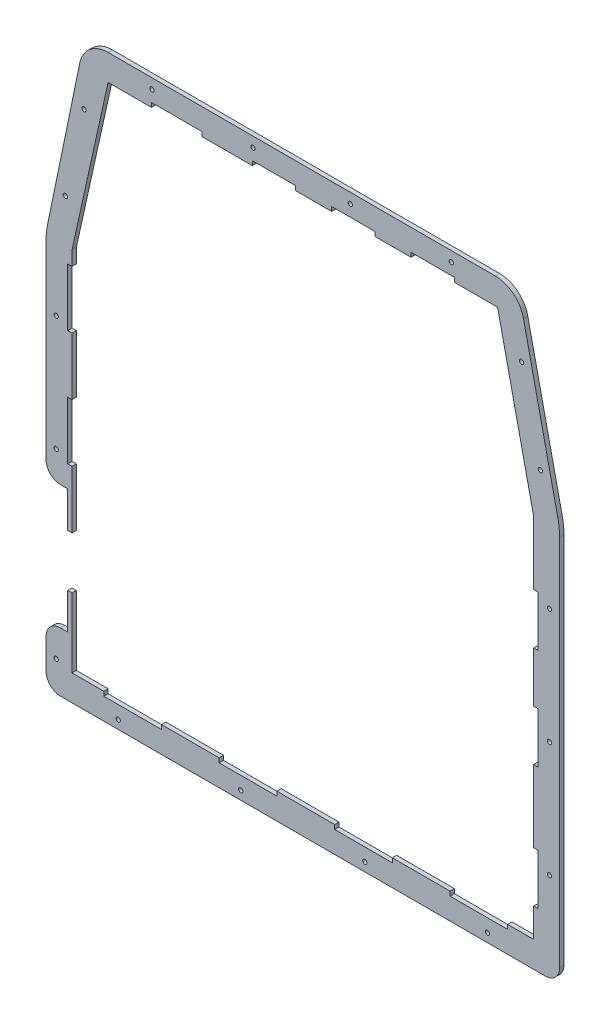
SolidWorks part; units mm, degrees
ref_plane "Front Plane" through (0, 0, 0) normal (0, 0, 1) x (1, 0, 0)
ref_plane "Top Plane" through (0, 0, 0) normal (0, 1, 0) x (1, 0, 0)
ref_plane "Right Plane" through (0, 0, 0) normal (1, 0, 0) x (0, 0, -1)
ref_plane "Plane1" through (0, 0, -1194.953) normal (0, 0, 1) x (1, 0, 0)
sketch "Sketch1" plane through (0, 0, -1194.953) normal (0, 0, 1) x (1, 0, 0)
  line L1 (-160, 1173.2804) -> (160, 1173.2804)
  line L2 (160, 1173.2804) -> (160, 1427.2804)
  line L3 (-135, 1540.2804) -> (135, 1540.2804)
  line L4 (-139, 1540.2804) -> (-105, 1540.2804) construction
  line L5 (160, 1427.2804) -> (135, 1540.2804)
  line L6 (-160, 1173.2804) -> (-160, 1282.2804)
  line L8 (-154.5872, 1542.3231) -> (-176.9679, 1433.8872)
  line L9 (152.9219, 1542.6007) -> (176.8195, 1434.5836)
  line L10 (-168, 1155.2804) -> (168, 1155.2804)
  line L11 (178, 1165.2804) -> (178, 1423.7829)
  line L12 (133.3941, 1558.2804) -> (-135, 1558.2804)
  line L13 (-178, 1423.7804) -> (-178, 1292.2804)
  line L15 (-168, 1196.2804) -> (-163, 1196.2804)
  line L20 (-178, 1186.2804) -> (-178, 1165.2804)
  line L21 (-168, 1282.2804) -> (-163, 1282.2804)
  line L22 (-163, 1427.2804) -> (-163, 1417.2804) construction
  line L23 (-163, 1282.2804) -> (-163, 1196.2804)
  line L25 (-160, 1427.2804) -> (-160, 1282.2804)
  line L26 (-135, 1540.2804) -> (-160, 1427.2804)
  arc A0 (152.9219, 1542.6007) -> (133.3941, 1558.2804) centre (133.3941, 1538.2804) ccw
  arc A1 (-154.5872, 1542.3231) -> (-135, 1558.2804) centre (-135, 1538.2804) cw
  arc A2 (168, 1155.2804) -> (178, 1165.2804) centre (168, 1165.2804) ccw
  arc A3 (-178, 1165.2804) -> (-168, 1155.2804) centre (-168, 1165.2804) ccw
  arc A4 (176.8195, 1434.5836) -> (178, 1423.7829) centre (128, 1423.7829) cw
  arc A5 (-176.9679, 1433.8872) -> (-178, 1423.7804) centre (-128, 1423.7804) ccw
  arc A6 (-168, 1196.2804) -> (-178, 1186.2804) centre (-168, 1186.2804) ccw
  arc A7 (-168, 1282.2804) -> (-178, 1292.2804) centre (-168, 1292.2804) cw
  circle A8 centre (-171, 1176.2804) radius 1.5
  circle A9 centre (-128, 1161.2804) radius 1.5
  circle A10 centre (-43, 1161.2804) radius 1.5
  circle A11 centre (43, 1161.2804) radius 1.5
  circle A12 centre (128, 1161.2804) radius 1.5
  circle A13 centre (171, 1217.2804) radius 1.5
  circle A14 centre (171, 1297.2804) radius 1.5
  circle A15 centre (171, 1377.2804) radius 1.5
  circle A16 centre (151.6679, 1515.8638) radius 1.5
  circle A17 centre (164.6288, 1457.2804) radius 1.5
  circle A18 centre (-104.5872, 1551.2804) radius 1.5
  circle A19 centre (-34.5872, 1551.2804) radius 1.5
  circle A20 centre (32.9219, 1551.2804) radius 1.5
  circle A21 centre (102.9219, 1551.2804) radius 1.5
  circle A22 centre (-171, 1382.2804) radius 1.5
  circle A23 centre (-171, 1302.2804) radius 1.5
  circle A24 centre (-151.6679, 1515.8638) radius 1.5
  circle A25 centre (-164.6288, 1457.2804) radius 1.5
  point P41 (-178, 1196.2804)
  dimension "D9" = 20
  dimension "D10" = 10
  dimension "D11" = 50
  dimension "D14" = 10
  dimension "D5" = 25
  dimension "D16" = 3
  dimension "D17" = 3
  dimension "D18" = 20
  dimension "D19" = 11
  dimension "D20" = 3
  dimension "D21" = 80
  dimension "D22" = 3
  dimension "D23" = 11
  dimension "D24" = 11
  dimension "D25" = 30
  dimension "D26" = 3
  dimension "D27" = 11
  dimension "D28" = 60
  dimension "D29" = 3
  dimension "D30" = 50
  dimension "D31" = 3
  dimension "D32" = 3
  dimension "D33" = 3
  dimension "D34" = 70
  dimension "D36" = 70
  dimension "D37" = 7
  dimension "D38" = 7
  dimension "D41" = 3
  dimension "D42" = 3
  dimension "D43" = 30
  dimension "D44" = 11
  dimension "D45" = 11
  dimension "D46" = 60
  dimension "D47" = 3
  dimension "D48" = 3
  dimension "D49" = 3
  dimension "D50" = 3
  dimension "D51" = 3
  dimension "D52" = 3
  dimension "D53" = 3
  dimension "D54" = 20
  dimension "D55" = 6
  dimension "D56" = 11
  dimension "D57" = 7
  dimension "D58" = 7
  dimension "D61" = 80
  dimension "D62" = 50
  dimension "D63" = 85
  dimension "D66" = 7
  dimension "D67" = 6
  dimension "D64" = 85
  dimension "D1" = 18
  dimension "D2" = 25
  dimension "D3" = 18
  dimension "D4" = 270
  dimension "D6" = 18
  dimension "D7" = 18
  dimension "D8" = 18
  dimension "D12" = 23
  dimension "D13" = 86
  dimension "D15" = 134.5
  dimension "D35" = 50
  dimension "D39" = 7
  dimension "D40" = 7
  dimension "D59" = 50
  dimension "D60" = 80
  dimension "D65" = 50
  dimension "D68" = 6
  dimension "D69" = 6
extrude "Boss-Extrude1" add sketch "Sketch1" along normal blind 3 contours A7 L21 L23 L15 A6 L20 A3 L10 A2 L11 A4 L9 A0 L12 A1 L8 A5 L13 L6 L25 L26 L3 L5 L2 L1
sketch "Sketch2" plane through (0, 0, -1191.953) normal (0, 0, 1) x (1, 0, 0)
  line L0 (-160, 1173.2804) -> (160, 1173.2804) construction
  line L1 (-138, 1173.2804) -> (-98, 1173.2804)
  line L2 (-138, 1173.2804) -> (-138, 1170.2804)
  line L3 (-138, 1170.2804) -> (-98, 1170.2804)
  line L4 (-98, 1173.2804) -> (-98, 1170.2804)
  line L5 (-163, 1170.2804) -> (-138, 1170.2804) construction
  line L6 (-58, 1173.2804) -> (-18, 1173.2804)
  line L7 (-58, 1173.2804) -> (-58, 1170.2804)
  line L8 (-58, 1170.2804) -> (-18, 1170.2804)
  line L9 (-18, 1173.2804) -> (-18, 1170.2804)
  line L10 (-178, 1186.2804) -> (-178, 1165.2804) construction
  line L11 (22, 1173.2804) -> (62, 1173.2804)
  line L12 (22, 1173.2804) -> (22, 1170.2804)
  line L13 (22, 1170.2804) -> (62, 1170.2804)
  line L14 (62, 1173.2804) -> (62, 1170.2804)
  line L15 (102, 1173.2804) -> (142, 1173.2804)
  line L16 (102, 1173.2804) -> (102, 1170.2804)
  line L17 (102, 1170.2804) -> (142, 1170.2804)
  line L18 (142, 1173.2804) -> (142, 1170.2804)
  line L19 (-163, 1282.2804) -> (-163, 1196.2804) construction
  line L20 (-163, 1257.2804) -> (-160, 1257.2804)
  line L21 (-163, 1257.2804) -> (-163, 1221.2804)
  line L22 (-163, 1221.2804) -> (-160, 1221.2804)
  line L23 (-160, 1257.2804) -> (-160, 1221.2804)
  line L24 (-160, 1173.2804) -> (-160, 1427.2804) construction
  line L25 (-168, 1196.2804) -> (-163, 1196.2804) construction
  line L26 (-168, 1282.2804) -> (-163, 1282.2804) construction
  line L28 (-160, 1297.2804) -> (-163, 1297.2804)
  line L29 (-160, 1297.2804) -> (-160, 1337.2804)
  line L30 (-160, 1337.2804) -> (-163, 1337.2804)
  line L31 (-163, 1297.2804) -> (-163, 1337.2804)
  line L32 (-160, 1377.2804) -> (-163, 1377.2804)
  line L33 (-160, 1377.2804) -> (-160, 1417.2804)
  line L34 (-160, 1417.2804) -> (-163, 1417.2804)
  line L35 (-163, 1377.2804) -> (-163, 1417.2804)
  line L44 (-135, 1540.2804) -> (135, 1540.2804) construction
  line L45 (-105, 1540.2804) -> (-70, 1540.2804)
  line L46 (-105, 1540.2804) -> (-105, 1543.2804)
  line L47 (-105, 1543.2804) -> (-70, 1543.2804)
  line L48 (-70, 1540.2804) -> (-70, 1543.2804)
  line L49 (-139, 1543.2804) -> (-105, 1543.2804) construction
  line L51 (-35, 1540.2804) -> (-5, 1540.2804)
  line L52 (-35, 1540.2804) -> (-35, 1543.2804)
  line L53 (-35, 1543.2804) -> (-5, 1543.2804)
  line L54 (-5, 1540.2804) -> (-5, 1543.2804)
  line L55 (20, 1540.2804) -> (50, 1540.2804)
  line L56 (20, 1540.2804) -> (20, 1543.2804)
  line L57 (20, 1543.2804) -> (50, 1543.2804)
  line L58 (50, 1540.2804) -> (50, 1543.2804)
  line L59 (75, 1540.2804) -> (105, 1540.2804)
  line L60 (75, 1540.2804) -> (75, 1543.2804)
  line L61 (75, 1543.2804) -> (105, 1543.2804)
  line L62 (105, 1540.2804) -> (105, 1543.2804)
  line L76 (160, 1313.2804) -> (163, 1313.2804)
  line L77 (160, 1173.2804) -> (160, 1427.2804) construction
  line L78 (160, 1193.2804) -> (163, 1193.2804)
  line L79 (160, 1193.2804) -> (160, 1228.2804)
  line L80 (160, 1228.2804) -> (163, 1228.2804)
  line L81 (163, 1193.2804) -> (163, 1228.2804)
  line L82 (163, 1427.2804) -> (163, 1383.2804) construction
  line L83 (160, 1313.2804) -> (160, 1278.2804)
  line L84 (160, 1383.2804) -> (163, 1383.2804)
  line L85 (160, 1383.2804) -> (160, 1348.2804)
  line L86 (160, 1348.2804) -> (163, 1348.2804)
  line L87 (163, 1383.2804) -> (163, 1348.2804)
  line L88 (160, 1278.2804) -> (163, 1278.2804)
  line L89 (163, 1313.2804) -> (163, 1278.2804)
  dimension "D1" = 40
  dimension "D2" = 40
  dimension "D3" = 3
  dimension "D4" = 40
  dimension "D5" = 40
  dimension "D6" = 3
  dimension "D7" = 40
  dimension "D8" = 40
  dimension "D9" = 3
  dimension "D10" = 40
  dimension "D11" = 40
  dimension "D12" = 25
  dimension "D13" = 25
  dimension "D14" = 40
  dimension "D15" = 40
  dimension "D16" = 3
  dimension "D17" = 40
  dimension "D18" = 40
  dimension "D19" = 3
  dimension "D26" = 30
  dimension "D27" = 35
  dimension "D28" = 35
  dimension "D29" = 30
  dimension "D30" = 25
  dimension "D31" = 3
  dimension "D32" = 3
  dimension "D33" = 3
  dimension "D34" = 30
  dimension "D35" = 25
  dimension "D36" = 30
  dimension "D43" = 20
  dimension "D44" = 35
  dimension "D45" = 50
  dimension "D46" = 35
  dimension "D47" = 3
  dimension "D48" = 35
  dimension "D49" = 35
extrude "Cut-Extrude1" cut sketch "Sketch2" against normal blind 3
